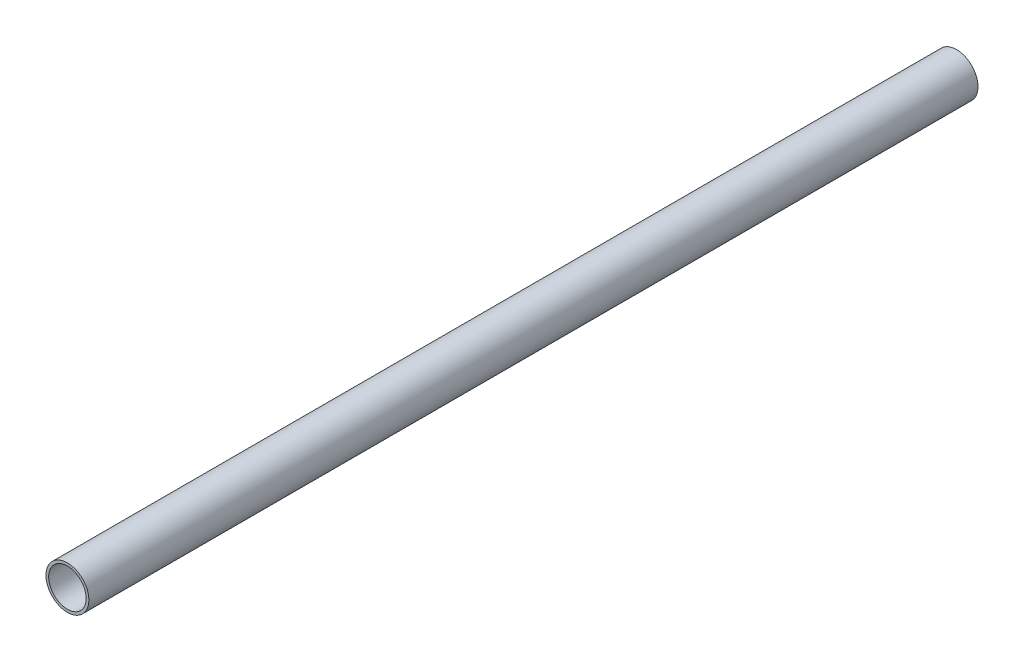
SolidWorks part; units mm, degrees
ref_plane "Plano frontal" through (0, 0, 0) normal (0, 0, 1) x (1, 0, 0)
ref_plane "Plano superior" through (0, 0, 0) normal (0, 1, 0) x (1, 0, 0)
ref_plane "Plano direito" through (0, 0, 0) normal (1, 0, 0) x (0, 0, -1)
sketch "Sketch2" plane through (0, 0, 0) normal (0, 0, 1) x (1, 0, 0)
  circle A0 centre (2449.7201, -5187.0074) radius 24.125
  circle A1 centre (2449.7201, -5187.0074) radius 21.075
  dimension "D1" = 3.05
extrude "Boss-Extrude1" add sketch "Sketch2" along normal blind 1000
